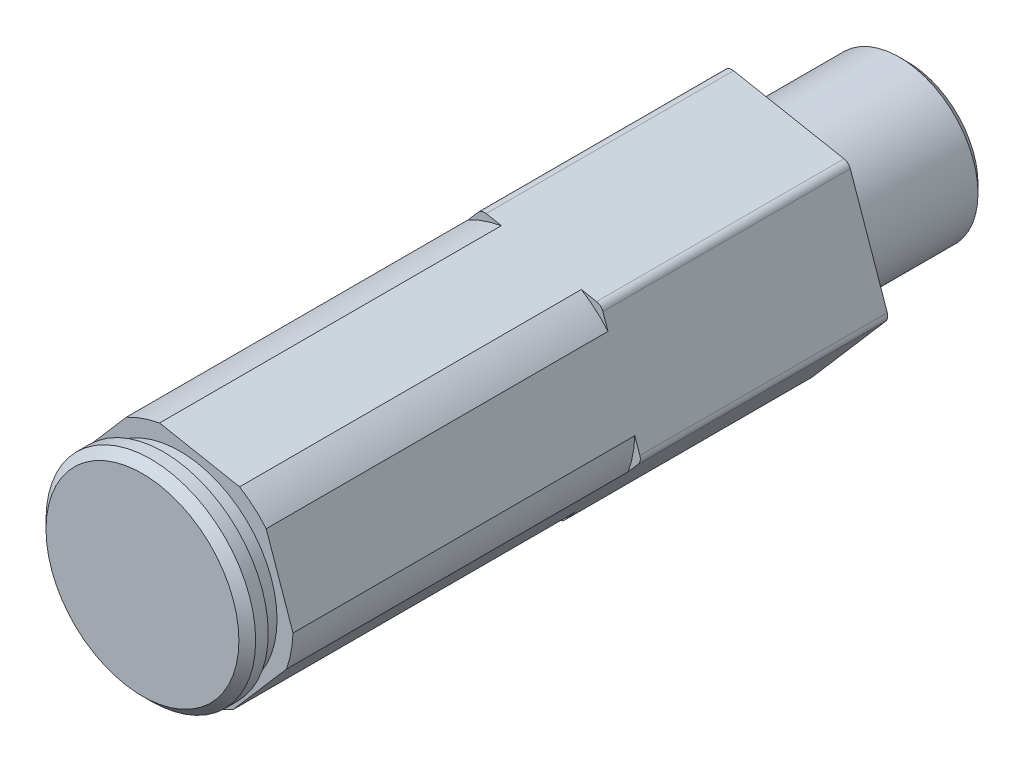
SolidWorks part; units mm, degrees
material "6061-T6 (SS)"
ref_plane "Front Plane" through (0, 0, 0) normal (0, 0, 1) x (1, 0, 0)
ref_plane "Top Plane" through (0, 0, 0) normal (0, 1, 0) x (1, 0, 0)
ref_plane "Right Plane" through (0, 0, 0) normal (1, 0, 0) x (0, 0, -1)
sketch "Sketch2" plane through (0, 0, 0) normal (1, 0, 0) x (0, 0, -1)
  line L0 (-23.1775, 0) -> (23.1775, 0)
  line L1 (23.1775, 0) -> (23.1775, 4.7625)
  line L6 (22.6695, 4.7625) -> (14.7701, 4.7625)
  line L7 (14.7701, 4.7625) -> (14.7701, 6.8623)
  line L8 (14.7701, 6.8623) -> (-20.9169, 6.8623)
  line L9 (-20.9169, 6.8623) -> (-20.9169, 5.8928)
  line L10 (-20.9169, 5.8928) -> (-21.9075, 5.8928)
  line L11 (-21.9075, 5.8928) -> (-21.9075, 6.35)
  line L12 (-21.9075, 6.35) -> (-23.1775, 6.35)
  line L13 (-23.1775, 6.35) -> (-23.1775, 0)
  line L14 (-34.6685, 0) -> (43.2094, 0) construction
  line L15 (22.6695, 4.7625) -> (23.1775, 4.7625)
  point P18 (0, 0)
  dimension "D1" = 35.687
  dimension "D2" = 7.8994
  dimension "D3" = 0.508
  dimension "D4" = 1.27
  dimension "D5" = 9.525
  dimension "D6" = 13.7246
  dimension "D7" = 11.7856
  dimension "D8" = 12.7
  dimension "D11" = 0.9906
revolve "Revolve1" add sketch "Sketch2" angle 360 about L0
sketch "Sketch3" plane through (0, 0, 23.1775) normal (0, 0, 1) x (1, 0, 0)
  line L1 (7.2629, -1.3857) -> (4.8315, 5.597)
  line L2 (4.8315, 5.597) -> (-2.4314, 6.9827)
  line L3 (-2.4314, 6.9827) -> (-7.2629, 1.3857)
  line L4 (-7.2629, 1.3857) -> (-4.8315, -5.597)
  line L5 (-4.8315, -5.597) -> (2.4314, -6.9827)
  line L6 (2.4314, -6.9827) -> (7.2629, -1.3857)
  circle A0 centre (0, 0) radius 6.4033 construction
  dimension "D1" = 12.8067
extrude "Cut-Extrude1" cut sketch "Sketch3" against normal through all flip side to cut
sketch "Sketch4" plane through (0, 0, -23.1775) normal (0, 0, -1) x (-1, 0, 0)
  circle A0 centre (0, 0) radius 2.54 construction
  dimension "D1" = 5.08
hole_wizard "1/4 (0.25) Diameter Hole1" positions "Sketch5" profile "Sketch6" hole size "1/4" standard "ANSI Inch"
sketch "Sketch5" plane through (0, 0, -23.1775) normal (0, 0, -1) x (-1, 0, 0)
  point P0 (0, 0)
sketch "Sketch6" plane through (0, 0, -23.1775) normal (1, 0, 0) x (0, 1, 0)
  line L0 (0, 0) -> (0, 10.6453)
  line L1 (0, 10.6453) -> (3.175, 8.7376)
  line L2 (3.175, 8.7376) -> (3.175, 0)
  line L5 (3.175, 0) -> (0, 0)
  line L10 (0, 10.6453) -> (-3.175, 8.7376) construction
  line L11 (0, -6.35) -> (0, 107.95) construction
  dimension "Hole Dia." = 6.35
  dimension "Hole Depth" = 8.7376
  dimension "Drill Angle" = 118
chamfer "Chamfer1" distance 0.508 angle 45 2 edges at (6.35, 0, 23.1775) (4.7625, 0, -23.1775)
sketch "Sketch7" plane through (0, 0, -14.7701) normal (0, 0, -1) x (-1, 0, 0)
  line L0 (-3.6238, 5.8274) -> (1.2237, 6.7523) construction
  line L1 (-4.8315, 5.597) -> (-7.2629, -1.3857)
  line L2 (-7.2629, -1.3857) -> (-2.4314, -6.9827)
  line L3 (-2.4314, -6.9827) -> (4.8315, -5.597)
  line L4 (4.8315, -5.597) -> (7.2629, 1.3857)
  line L5 (7.2629, 1.3857) -> (2.4314, 6.9827)
  line L6 (2.4314, 6.9827) -> (-4.8315, 5.597)
  circle A0 centre (0, 0) radius 6.4033 construction
  circle A1 centre (0, 0) radius 3.175 construction
  circle A2 centre (0, 0) radius 3.175
extrude "Boss-Extrude1" add sketch "Sketch7" against normal offset from surface (14.986 mm away) 20.701 up to face at (5.8928, 0, 20.9169)
fillet "Fillet1" radius 0.508 6 edges at (7.2629, -1.3857, -7.2771) (-2.4314, 6.9827, -7.2771) (-7.2629, 1.3857, -7.2771) (-4.8315, -5.597, -7.2771) (2.4314, -6.9827, -7.2771) (4.8315, 5.597, -7.2771)
